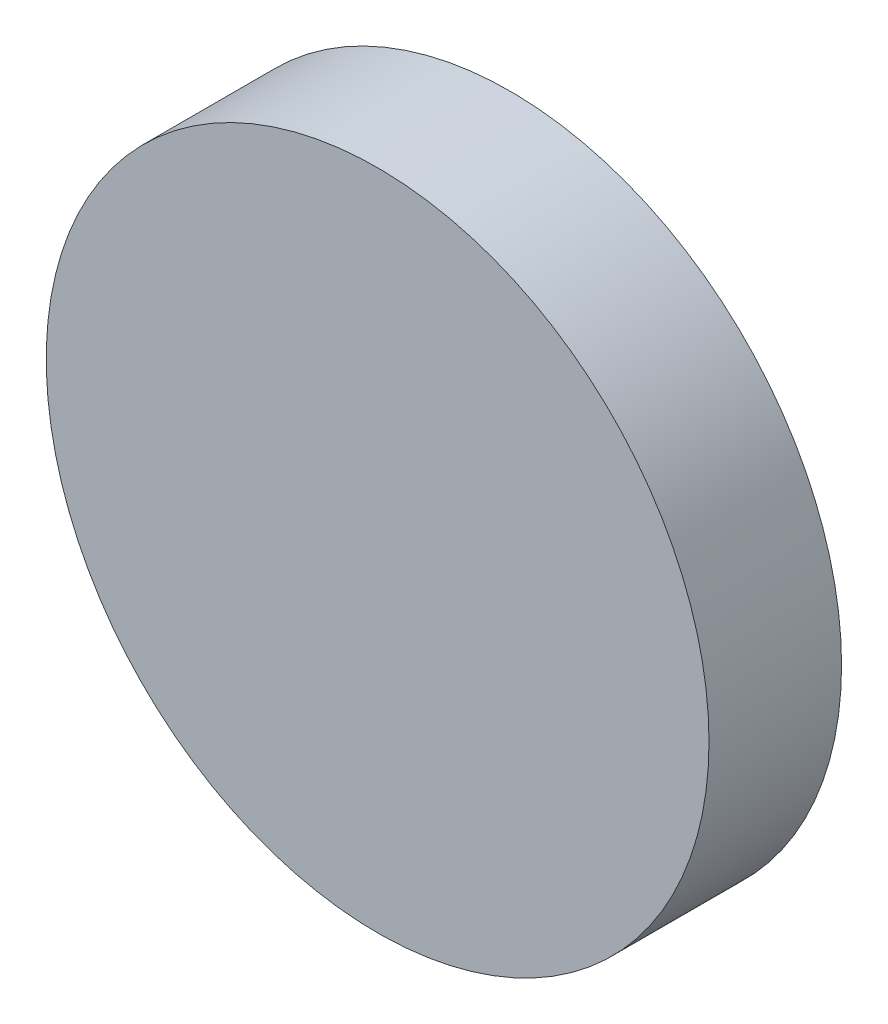
SolidWorks part; units mm, degrees
ref_plane "Plan de face" through (0, 0, 0) normal (0, 0, 1) x (1, 0, 0)
ref_plane "Plan de dessus" through (0, 0, 0) normal (0, 1, 0) x (1, 0, 0)
ref_plane "Plan de droite" through (0, 0, 0) normal (1, 0, 0) x (0, 0, -1)
sketch "Esquisse2" plane through (0, 0, 0) normal (0, 0, 1) x (1, 0, 0)
  circle A0 centre (0, 0) radius 2.5
  dimension "D1" = 5
extrude "Boss.-Extru.1" add sketch "Esquisse2" along normal mid plane 1
